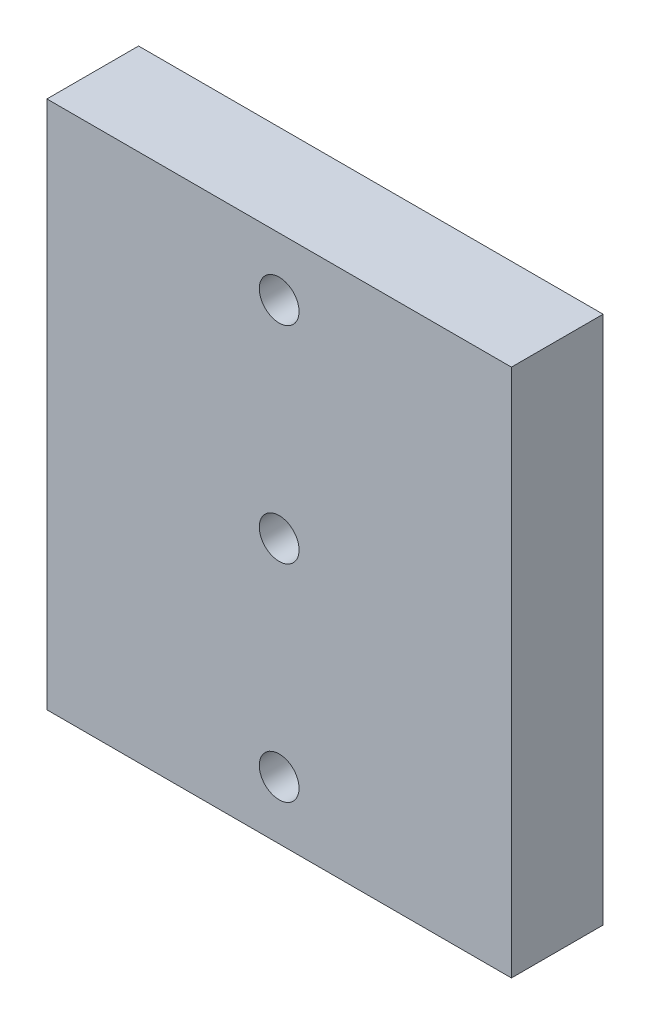
SolidWorks part; units mm, degrees
ref_plane "Front Plane" through (0, 0, 0) normal (0, 0, 1) x (1, 0, 0)
ref_plane "Top Plane" through (0, 0, 0) normal (0, 1, 0) x (1, 0, 0)
ref_plane "Right Plane" through (0, 0, 0) normal (1, 0, 0) x (0, 0, -1)
sketch "Sketch1" plane through (0, 0, 0) normal (0, 0, 1) x (1, 0, 0)
  line L1 (-114.3, 130.175) -> (114.3, 130.175)
  line L2 (-114.3, 130.175) -> (-114.3, -130.175)
  line L3 (-114.3, -130.175) -> (114.3, -130.175)
  line L4 (114.3, 130.175) -> (114.3, -130.175)
  line L5 (-114.3, 130.175) -> (114.3, -130.175) construction
  line L6 (-114.3, -130.175) -> (114.3, 130.175) construction
  point P0 (0, 0)
  dimension "D1" = 228.6
  dimension "D2" = 260.35
extrude "Boss-Extrude1" add sketch "Sketch1" along normal blind 45.1104
sketch "Sketch2" plane through (0, 0, 45.1104) normal (0, 0, 1) x (1, 0, 0)
  line L0 (-114.3, 0) -> (114.3, 0) construction
  line L5 (-114.3, 130.175) -> (-114.3, -130.175) construction
  line L6 (114.3, -130.175) -> (114.3, 130.175) construction
  line L7 (-114.3, -101.6) -> (114.3, -101.6) construction
  line L8 (-114.3, 101.6) -> (114.3, 101.6) construction
  line L9 (0, 101.6) -> (0, -101.6) construction
  line L10 (127, 101.6) -> (127, -101.6) construction
  line L11 (-127, 101.6) -> (-127, -101.6) construction
  circle A4 centre (0, 0) radius 6.5151
  circle A5 centre (0, 101.6) radius 6.5151
  circle A6 centre (0, -101.6) radius 6.5151
  dimension "D5" = 13.0302
  dimension "D1" = 101.6
  dimension "D2" = 101.6
  dimension "D3" = 127
  dimension "D4" = 127
extrude "HAAS T-Slot Holes" cut sketch "Sketch2" against normal through all
sketch "Sketch3" plane through (0, 0, 45.1104) normal (0, 0, 1) x (1, 0, 0)
  circle A0 centre (0, 101.6) radius 9.779
  circle A2 centre (0, 0) radius 9.779
  circle A4 centre (0, -101.6) radius 9.779
  circle A5 centre (0, 101.6) radius 6.5151 construction
  circle A6 centre (0, -101.6) radius 6.5151 construction
  dimension "D1" = 19.558
extrude "HAAS Counter Bores" cut sketch "Sketch3" against normal offset from surface (35.5854 mm away) 9.525 up to face at (6.5151, 101.6, 0)
